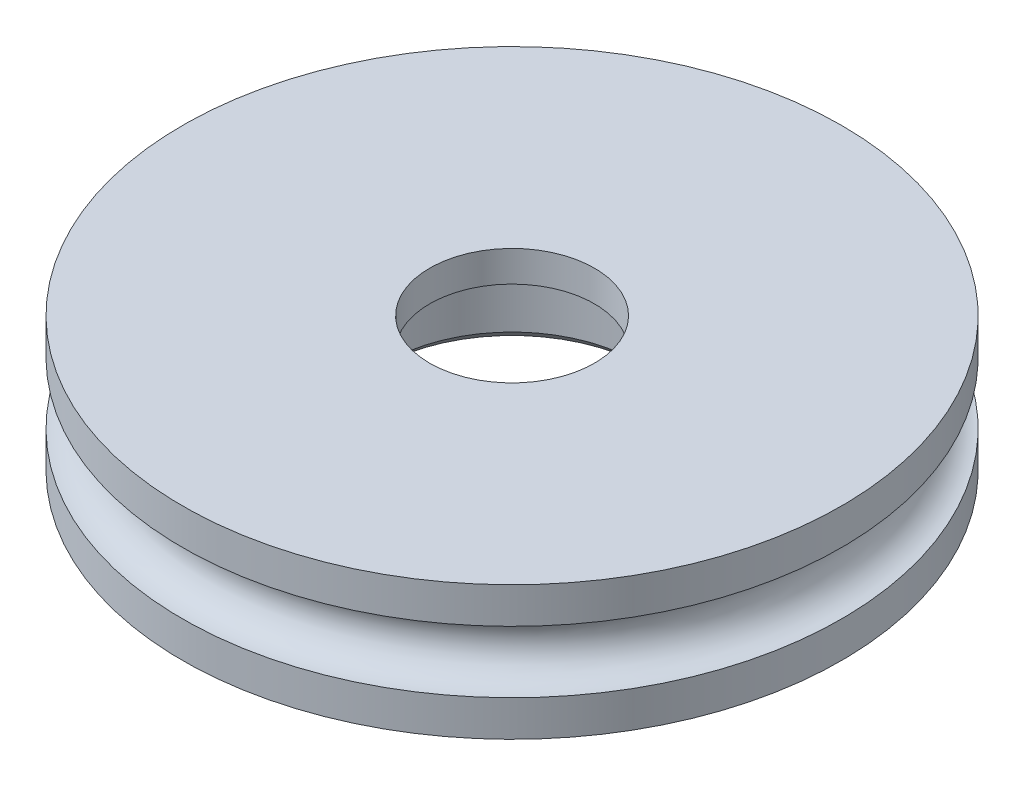
SolidWorks part; units mm, degrees
ref_plane "Front Plane" through (0, 0, 0) normal (0, 0, 1) x (1, 0, 0)
ref_plane "Top Plane" through (0, 0, 0) normal (0, 1, 0) x (1, 0, 0)
ref_plane "Right Plane" through (0, 0, 0) normal (1, 0, 0) x (0, 0, -1)
sketch "Sketch1" plane through (0, 0, 0) normal (0, 1, 0) x (1, 0, 0)
  circle A2 centre (0, 0) radius 3.05
  circle A3 centre (0, 0) radius 8
  dimension "D1" = 6.1
  dimension "D2" = 16
extrude "Boss-Extrude1" add sketch "Sketch1" along normal mid plane 3.25
sketch "Sketch2" plane through (0, 0, 0) normal (1, 0, 0) x (0, 0, -1)
  line L0 (-8, -1.625) -> (-8, -0.75) construction
  line L1 (-8, 1.625) -> (-8, -1.625) construction
  line L2 (-8, 1.625) -> (-8, 0.75) construction
  line L3 (-8, 0.75) -> (-8, -0.75)
  line L4 (-8, -1.625) -> (8, -1.625) construction
  ellipse E0 centre (-8, 0) end of major axis (-8.75, 0) minor radius 0.75 (-8, -0.75) -> (-8, 0.75) ccw
  ellipse E1 centre (-8, 0) end of major axis (-7.25, 0) minor radius 0.75 (-8, 0.75) -> (-8, -0.75) ccw construction
  dimension "D1" = 1.5
  dimension "D3" = 0.875
  dimension "D4" = 0.75
revolve "Cut-Revolve1" cut sketch "Sketch2" angle 360 about axis through (0, 1.625, 0) along (0, -1, 0)
sketch "Sketch3" plane through (0, 1.625, 0) normal (0, 1, 0) x (1, 0, 0)
  circle A0 centre (0, 0) radius 3.5
  circle A1 centre (0, 0) radius 2
  dimension "D1" = 4
  dimension "D2" = 7
extrude "Boss-Extrude2" add sketch "Sketch3" against normal blind 0.75
sketch "Sketch4" plane through (0, -1.625, 0) normal (0, -1, 0) x (1, 0, 0)
  circle A0 centre (0, 0) radius 6.5
  circle A1 centre (0, 0) radius 8 construction
  circle A2 centre (0, 0) radius 3
  dimension "D1" = 1.5
  dimension "D2" = 6
extrude "Cut-Extrude1" cut sketch "Sketch4" against normal blind 0.5
chamfer "Chamfer1" distance 0.25 angle 45 1 edges at (0, -1.125, -3.05)
